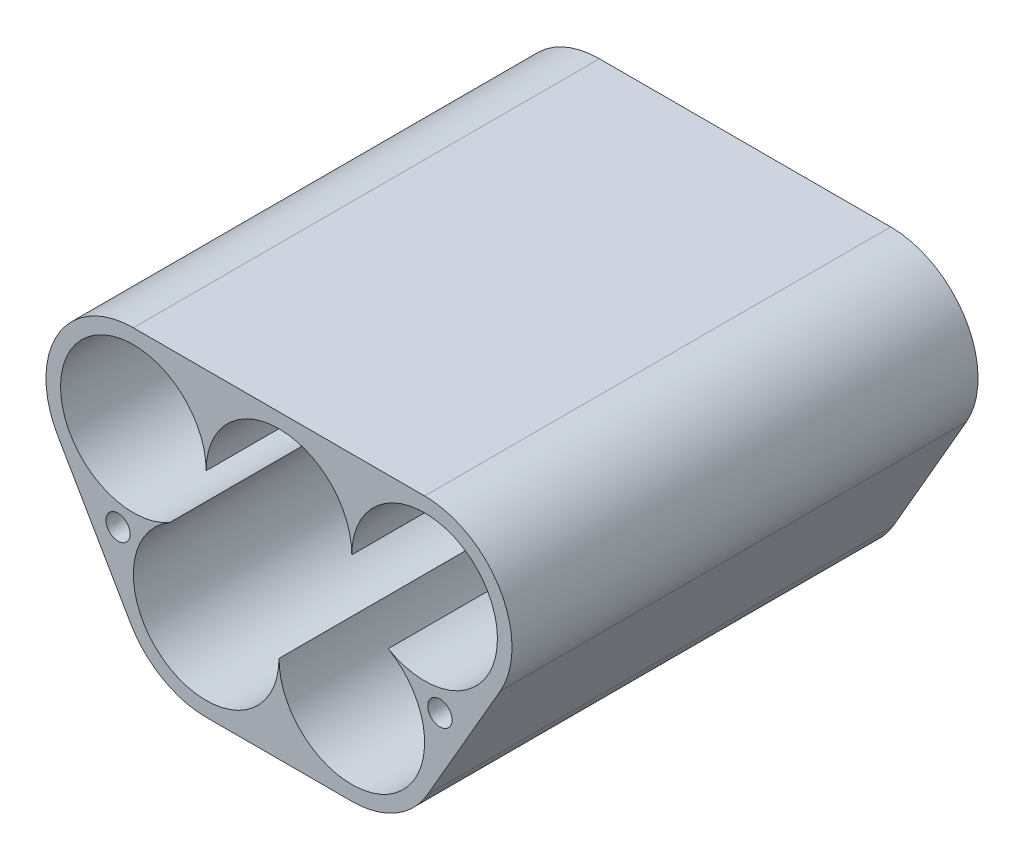
SolidWorks part; units mm, degrees
ref_plane "Front Plane" through (0, 0, 0) normal (0, 0, 1) x (1, 0, 0)
ref_plane "Top Plane" through (0, 0, 0) normal (0, 1, 0) x (1, 0, 0)
ref_plane "Right Plane" through (0, 0, 0) normal (1, 0, 0) x (0, 0, -1)
sketch "Sketch1" plane through (0, 0, 0) normal (0, 0, 1) x (1, 0, 0)
  line L4 (7.5, -21.9904) -> (22.5, -21.9904)
  line L5 (30.2942, -17.4904) -> (37.7942, -4.5)
  line L6 (30, 9) -> (0, 9)
  line L7 (-7.7942, -4.5) -> (-0.2942, -17.4904)
  line L8 (7.5, -21.9904) -> (22.5, -21.9904)
  line L9 (30.2942, -17.4904) -> (37.7942, -4.5)
  line L10 (30, 9) -> (0, 9)
  line L11 (-7.7942, -4.5) -> (-0.2942, -17.4904)
  arc A4 (22.5, -21.9904) -> (30.2942, -17.4904) centre (22.5, -12.9904) ccw
  arc A5 (37.7942, -4.5) -> (30, 9) centre (30, 0) ccw
  arc A6 (0, 9) -> (-7.7942, -4.5) centre (0, 0) ccw
  arc A7 (-0.2942, -17.4904) -> (7.5, -21.9904) centre (7.5, -12.9904) ccw
  arc A8 (22.5, -21.9904) -> (30.2942, -17.4904) centre (22.5, -12.9904) ccw
  arc A9 (37.7942, -4.5) -> (30, 9) centre (30, 0) ccw
  arc A10 (0, 9) -> (-7.7942, -4.5) centre (0, 0) ccw
  arc A11 (-0.2942, -17.4904) -> (7.5, -21.9904) centre (7.5, -12.9904) ccw
  circle A99 centre (7.5, -12.9904) radius 7.5 construction
  circle A100 centre (22.5, -12.9904) radius 7.5 construction
  circle A101 centre (30, 0) radius 7.5 construction
  circle A102 centre (15, 0) radius 7.5 construction
  circle A103 centre (0, 0) radius 7.5 construction
  arc A104 (3.75, -6.4952) -> (15, -12.9904) centre (7.5, -12.9904) ccw
  arc A105 (15, -12.9904) -> (26.25, -6.4952) centre (22.5, -12.9904) ccw
  arc A106 (26.25, -6.4952) -> (22.5, 0) centre (30, 0) ccw
  arc A107 (22.5, 0) -> (7.5, 0) centre (15, 0) ccw
  arc A108 (7.5, 0) -> (3.75, -6.4952) centre (0, 0) ccw
  dimension "D1" = 0
extrude "Boss-Extrude1" add sketch "Sketch1" along normal blind 48
sketch "Sketch2" plane through (0, 0, 0) normal (0, 0, -1) x (-1, 0, 0)
  circle A0 centre (1.5761, -9.5702) radius 2.75 construction
  circle A1 centre (-31.575, -9.5702) radius 2.75 construction
  circle A2 centre (1.5761, -9.5702) radius 2.75 construction
  circle A3 centre (-31.575, -9.5702) radius 2.75 construction
  circle A4 centre (1.5761, -9.5702) radius 1.25
  circle A5 centre (-31.575, -9.5702) radius 1.25
  dimension "D1" = 2.5
extrude "Cut-Extrude1" cut sketch "Sketch2" against normal through all
